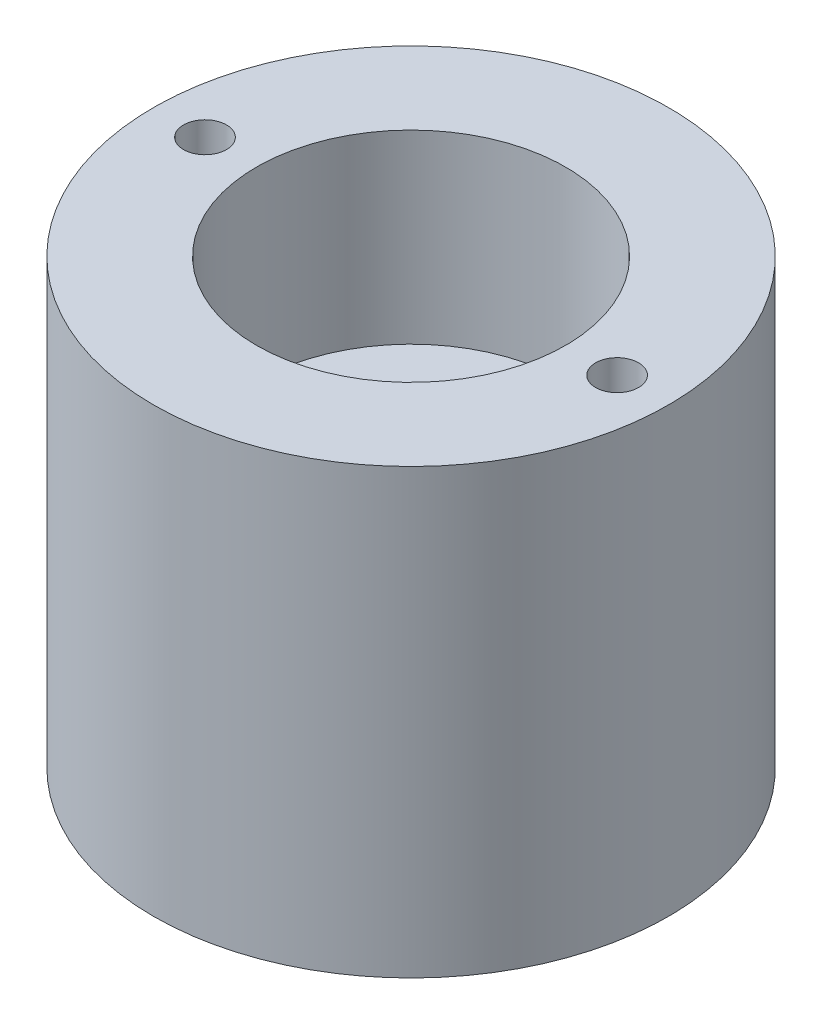
SolidWorks part; units mm, degrees
ref_plane "Спереди" through (0, 0, 0) normal (0, 0, 1) x (1, 0, 0)
ref_plane "Сверху" through (0, 0, 0) normal (0, 1, 0) x (1, 0, 0)
ref_plane "Справа" through (0, 0, 0) normal (1, 0, 0) x (0, 0, -1)
sketch "Эскиз1" plane through (0, 0, 0) normal (0, 1, 0) x (1, 0, 0)
  circle A0 centre (0, 0) radius 4
extrude "Бобышка-Вытянуть1" add sketch "Эскиз1" along normal blind 11
sketch "Эскиз2" plane through (0, 0, 0) normal (0, -1, 0) x (1, 0, 0)
  circle A0 centre (0, 0) radius 3.01
extrude "Вырез-Вытянуть2" cut sketch "Эскиз2" against normal blind 2
sketch "Эскиз3" plane through (0, 2, 0) normal (0, -1, 0) x (1, 0, 0)
  circle A0 centre (0, 0) radius 2.5
extrude "Вырез-Вытянуть3" cut sketch "Эскиз3" against normal blind 4.3 contours A0
sketch "Эскиз4" plane through (0, 6.3, 0) normal (0, -1, 0) x (1, 0, 0)
  line L1 (1.005, 2.005) -> (-1.005, 2.005)
  line L2 (1.005, 2.005) -> (1.005, -2.005)
  line L3 (1.005, -2.005) -> (-1.005, -2.005)
  line L4 (-1.005, 2.005) -> (-1.005, -2.005)
extrude "Вырез-Вытянуть4" cut sketch "Эскиз4" against normal blind 0.7
sketch "Эскиз5" plane through (0, 7, 0) normal (0, -1, 0) x (1, 0, 0)
  circle A0 centre (0, 0) radius 2.5
extrude "Вырез-Вытянуть5" cut sketch "Эскиз5" against normal blind 1
sketch "Эскиз7" plane through (0, 8, 0) normal (0, -1, 0) x (1, 0, 0)
  circle A0 centre (0, 0) radius 4
extrude "Вырез-Вытянуть6" cut sketch "Эскиз7" against normal blind 10
sketch "Эскиз12" plane through (0, 0, 0) normal (0, -1, 0) x (1, 0, 0)
  circle A0 centre (0, 0) radius 3.25
extrude "Вырез-Вытянуть7" cut sketch "Эскиз12" against normal blind 2
cosmetic thread "Условное изображение резьбы1" parameters "D1"=1.5, "D2"=7
sketch "Эскиз13" plane through (0, 8, 0) normal (0, 1, 0) x (1, 0, 0)
  circle A0 centre (0, 0) radius 2.5
  circle A1 centre (0, 0) radius 4
extrude "Бобышка-Вытянуть2" add sketch "Эскиз13" along normal blind 2
sketch "Эскиз14" plane through (0, 10, 0) normal (0, 1, 0) x (1, 0, 0)
  circle A2 centre (0, 0) radius 4
  circle A3 centre (0, 0) radius 2.5
extrude "Вырез-Вытянуть8" cut sketch "Эскиз14" against normal blind 3
sketch "Эскиз15" plane through (0, 7, 0) normal (0, 1, 0) x (1, 0, 0)
  circle A0 centre (0, 0) radius 7
  circle A1 centre (0, 0) radius 5
extrude "Бобышка-Вытянуть3" add sketch "Эскиз15" along normal blind 14.9 separate body
sketch "Эскиз16" plane through (0, 7, 0) normal (0, -1, 0) x (1, 0, 0)
  circle A0 centre (0, 0) radius 4
  circle A1 centre (0, 0) radius 7
extrude "Бобышка-Вытянуть4" add sketch "Эскиз16" along normal blind 7
sketch "Эскиз17" plane through (0, 21.9, 0) normal (0, 1, 0) x (1, 0, 0)
  circle A3 centre (6, 0) radius 0.8
  circle A4 centre (-6, 0) radius 0.8
extrude "Вырез-Вытянуть10" cut sketch "Эскиз17" against normal blind 5 contours A4 | A3
sketch "Эскиз18" plane through (0, 7, 0) normal (0, 1, 0) x (1, 0, 0)
  line L4 (-1.005, 1.505) -> (-1.005, -1.4942)
  line L5 (1.005, 1.505) -> (-1.005, 1.505)
  line L9 (1.005, -1.4942) -> (-1.005, -1.4942)
  line L10 (1.005, 1.505) -> (1.005, -1.4942)
  circle A0 centre (0, 0) radius 5
extrude "Бобышка-Вытянуть5" add sketch "Эскиз18" along normal blind 0.5
sketch "Эскиз20" plane through (0, 16.9, 0) normal (0, 1, 0) x (1, 0, 0)
  circle A0 centre (6, 0) radius 0.625
  circle A1 centre (-6, 0) radius 0.625
  circle A2 centre (-6, 0) radius 0.8 construction
extrude "Вырез-Вытянуть11" cut sketch "Эскиз20" against normal blind 9
cosmetic thread "Условное изображение резьбы2" parameters "D1"=4, "D2"=1.6
cosmetic thread "Условное изображение резьбы3" parameters "D1"=4, "D2"=1.6
sketch "Эскиз21" plane through (0, 21.9, 0) normal (0, 1, 0) x (1, 0, 0)
  circle A0 centre (0, 0) radius 7
extrude "Вырез-Вытянуть12" cut sketch "Эскиз21" against normal blind 9
sketch "Эскиз22" plane through (0, 12.9, 0) normal (0, 1, 0) x (1, 0, 0)
  circle A0 centre (0, 0) radius 7.5
  circle A1 centre (0, 0) radius 7
extrude "Бобышка-Вытянуть7" add sketch "Эскиз22" against normal blind 12.9
sketch "Эскиз23" plane through (0, 12.9, 0) normal (0, 1, 0) x (1, 0, 0)
  circle A0 centre (0, 0) radius 4.5
  circle A1 centre (0, 0) radius 5
extrude "Бобышка-Вытянуть8" add sketch "Эскиз23" against normal blind 10
